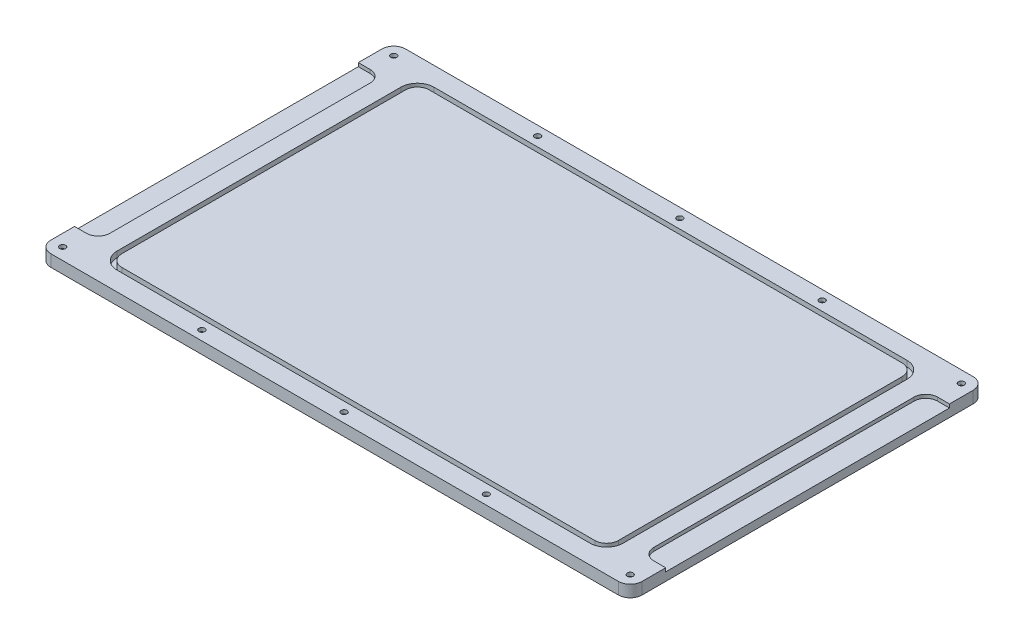
SolidWorks part; units mm, degrees
ref_plane "前视基准面" through (0, 0, 0) normal (0, 0, 1) x (1, 0, 0)
ref_plane "上视基准面" through (0, 0, 0) normal (0, 1, 0) x (1, 0, 0)
ref_plane "右视基准面" through (0, 0, 0) normal (1, 0, 0) x (0, 0, -1)
sketch "草图1" plane through (0, 0, 0) normal (0, 1, 0) x (1, 0, 0)
  line L1 (-120, 75) -> (120, 75)
  line L2 (-125, 70) -> (-125, -70)
  line L3 (-120, -75) -> (120, -75)
  line L4 (125, 70) -> (125, -70)
  line L5 (-125, 75) -> (125, -75) construction
  line L6 (-125, -75) -> (125, 75) construction
  arc A0 (125, 70) -> (120, 75) centre (120, 70) ccw
  arc A1 (125, -70) -> (120, -75) centre (120, -70) cw
  arc A2 (-125, -70) -> (-120, -75) centre (-120, -70) ccw
  arc A3 (-125, 70) -> (-120, 75) centre (-120, 70) cw
  point P0 (0, 0)
  dimension "D3" = 5
  dimension "D1" = 250
  dimension "D2" = 150
extrude "凸台-拉伸1" add sketch "草图1" along normal blind 5
sketch "草图2" plane through (0, 5, 0) normal (0, 1, 0) x (1, 0, 0)
  line L0 (-125, 70) -> (-125, -70) construction
  line L1 (-125, 60) -> (-120, 60)
  line L2 (-125, 60) -> (-125, -60)
  line L3 (-125, -60) -> (-120, -60)
  line L4 (-115, 55) -> (-115, -55)
  line L5 (0, 0) -> (0, 22.4955) construction
  line L6 (120, 75) -> (-120, 75) construction
  line L7 (-120, -75) -> (120, -75) construction
  line L8 (115, 55) -> (115, -55)
  line L9 (125, -60) -> (120, -60)
  line L10 (125, 60) -> (125, -60)
  line L11 (125, 60) -> (120, 60)
  arc A0 (-115, -55) -> (-120, -60) centre (-120, -55) cw
  arc A1 (-120, 60) -> (-115, 55) centre (-120, 55) cw
  arc A2 (120, 60) -> (115, 55) centre (120, 55) ccw
  arc A3 (115, -55) -> (120, -60) centre (120, -55) ccw
  point P11 (-122.5, -60)
  point P18 (-115, 60)
  point P27 (115, 60)
  dimension "D4" = 5
  dimension "D1" = 10
  dimension "D2" = 15
  dimension "D3" = 15
extrude "切除-拉伸1" cut sketch "草图2" against normal blind 1.5
sketch "草图3" plane through (0, 5, 0) normal (0, 1, 0) x (1, 0, 0)
  line L0 (120, 75) -> (-120, 75) construction
  line L1 (-100, 65) -> (100, 65)
  line L2 (-105, 60) -> (-105, -60)
  line L3 (-100, -65) -> (100, -65)
  line L4 (105, 60) -> (105, -60)
  line L5 (-105, 65) -> (105, -65) construction
  line L6 (-105, -65) -> (105, 65) construction
  line L7 (-115, -55) -> (-115, 55) construction
  line L8 (-100, 67) -> (100, 67)
  line L9 (107, 60) -> (107, -60)
  line L10 (-100, -67) -> (100, -67)
  line L11 (-107, 60) -> (-107, -60)
  arc A0 (105, -60) -> (100, -65) centre (100, -60) cw
  arc A1 (105, 60) -> (100, 65) centre (100, 60) ccw
  arc A2 (-105, -60) -> (-100, -65) centre (-100, -60) ccw
  arc A3 (-105, 60) -> (-100, 65) centre (-100, 60) cw
  arc A4 (107, 60) -> (100, 67) centre (100, 60) ccw
  arc A5 (107, -60) -> (100, -67) centre (100, -60) cw
  arc A6 (-107, -60) -> (-100, -67) centre (-100, -60) ccw
  arc A7 (-107, 60) -> (-100, 67) centre (-100, 60) cw
  point P1 (0, 0)
  dimension "D3" = 5
  dimension "D1" = 10
  dimension "D2" = 10
  dimension "D4" = 2
extrude "切除-拉伸2" cut sketch "草图3" against normal blind 2.5
sketch "草图4" plane through (0, 0, 0) normal (0, -1, 0) x (1, 0, 0)
  circle A0 centre (-120, 70) radius 1.25
  circle A1 centre (-120, -70) radius 1.25
  circle A2 centre (120, -70) radius 1.25
  circle A3 centre (120, 70) radius 1.25
  dimension "D1" = 2.5
  dimension "D2" = 2.5
  dimension "D3" = 2.5
  dimension "D4" = 2.5
extrude "切除-拉伸3" cut sketch "草图4" against normal blind 5
sketch "草图5" plane through (0, 0, 0) normal (0, -1, 0) x (1, 0, 0)
  circle A0 centre (-120, 70) radius 2.85
  circle A1 centre (-120, -70) radius 2.85
  circle A2 centre (120, -70) radius 2.85
  circle A3 centre (120, 70) radius 2.85
  dimension "D1" = 5.7
  dimension "D2" = 5.7
  dimension "D3" = 5.7
  dimension "D4" = 5.7
extrude "切除-拉伸4" cut sketch "草图5" against normal blind 3.5
sketch "草图6" plane through (0, 5, 0) normal (0, 1, 0) x (1, 0, 0)
  line L0 (0, 0) -> (0, 41.3894) construction
  line L1 (120, 75) -> (-120, 75) construction
  line L2 (120, 75) -> (-120, 75) construction
  line L3 (0, 0) -> (-38.2176, 0) construction
  circle A0 centre (0, 71) radius 1.25
  circle A1 centre (-60.1647, 71) radius 1.25
  circle A2 centre (60.1647, 71) radius 1.25
  circle A3 centre (60.1647, -71) radius 1.25
  circle A4 centre (-60.1647, -71) radius 1.25
  circle A5 centre (0, -71) radius 1.25
  dimension "D1" = 2.5
  dimension "D3" = 2.5
  dimension "D2" = 4
  dimension "D4" = 4
extrude "切除-拉伸5" cut sketch "草图6" against normal blind 5
sketch "草图7" plane through (0, 0, 0) normal (0, -1, 0) x (1, 0, 0)
  line L0 (0, 0) -> (9.1868, 0) construction
  circle A0 centre (-60.1647, 71) radius 2.85
  circle A1 centre (0, 71) radius 2.85
  circle A2 centre (60.1647, 71) radius 2.85
  circle A3 centre (60.1647, -71) radius 2.85
  circle A4 centre (0, -71) radius 2.85
  circle A5 centre (-60.1647, -71) radius 2.85
  dimension "D1" = 5.7
  dimension "D2" = 5.7
  dimension "D3" = 5.7
extrude "切除-拉伸6" cut sketch "草图7" against normal blind 3.5
